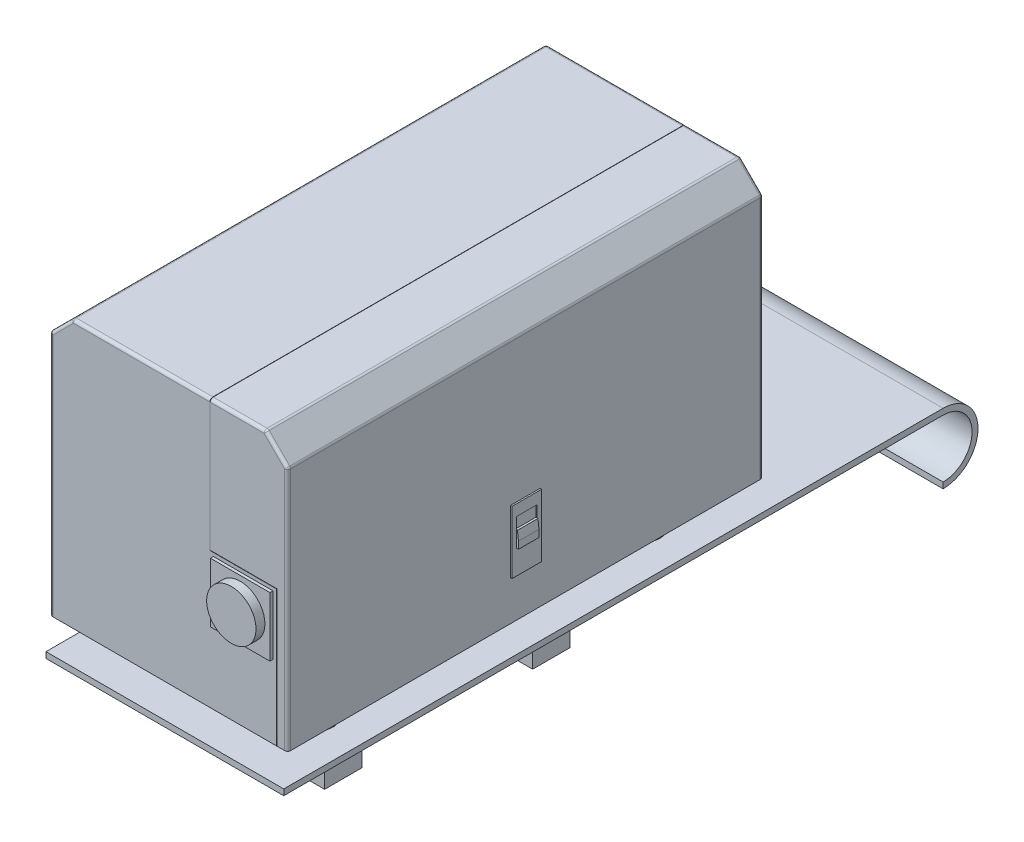
SolidWorks part; units mm, degrees
ref_plane "前视基准面" through (0, 0, 0) normal (0, 0, 1) x (1, 0, 0)
ref_plane "上视基准面" through (0, 0, 0) normal (0, 1, 0) x (1, 0, 0)
ref_plane "右视基准面" through (0, 0, 0) normal (1, 0, 0) x (0, 0, -1)
sketch "草图1" plane through (0, 0, 0) normal (0, 1, 0) x (1, 0, 0)
  line L1 (-80, -160) -> (80, -160)
  line L2 (-80, -160) -> (-80, 160)
  line L3 (-80, 160) -> (80, 160)
  line L4 (80, -160) -> (80, 160)
  line L5 (-80, -160) -> (80, 160) construction
  line L6 (-80, 160) -> (80, -160) construction
  point P0 (0, 0)
  dimension "D1" = 160
  dimension "D2" = 320
extrude "凸台-拉伸1" add sketch "草图1" along normal blind 180
sketch "草图2" plane through (0, 0, 160) normal (0, 0, 1) x (1, 0, 0)
  line L0 (27.8672, 180) -> (27.8672, 91.7238)
  line L1 (-80, 180) -> (80, 180) construction
  line L2 (27.8672, 91.7238) -> (72.7076, 91.7238)
  line L3 (72.7076, 91.7238) -> (72.7076, 0)
  line L4 (-80, 0) -> (80, 0) construction
extrude "切除-拉伸-薄壁3" cut sketch "草图2" along normal blind 0.2 and the other way through all thin
chamfer "倒角1" distance 15 angle 45 1 edges at (80, 180, 0)
chamfer "倒角2" distance 15 angle 45 1 edges at (-80, 180, 0)
fillet "圆角1" radius 2 8 edges at (80, 82.5, -160) (46.4336, 180, -160) (72.5, 172.5, -160) (80, 165, 0) (65, 180, 0) (72.5, 172.5, 160) (46.4336, 180, 160) (80, 82.5, 160)
fillet "圆角2" radius 2 8 edges at (-80, 82.5, -160) (-80, 165, 0) (-80, 82.5, 160) (-72.5, 172.5, -160) (-18.6664, 180, -160) (-65, 180, 0) (-72.5, 172.5, 160) (-18.6664, 180, 160)
sketch "草图3" plane through (80, 0, 0) normal (1, 0, 0) x (0, 0, -1)
  line L0 (0, 0) -> (0, 146.6557) construction
  line L2 (-9.9147, 26.7345) -> (9.9147, 26.7345)
  line L3 (-9.9147, 26.7345) -> (-9.9147, 68.9115)
  line L4 (-9.9147, 68.9115) -> (9.9147, 68.9115)
  line L5 (9.9147, 26.7345) -> (9.9147, 68.9115)
  line L6 (-9.9147, 26.7345) -> (9.9147, 68.9115) construction
  line L7 (-9.9147, 68.9115) -> (9.9147, 26.7345) construction
  point P3 (0, 47.823)
extrude "凸台-拉伸2" add sketch "草图3" along normal blind 1 separate body
sketch "草图4" plane through (81, 0, 0) normal (1, 0, 0) x (0, 0, -1)
  line L0 (0, 68.9115) -> (0, 26.3346) construction
  line L1 (9.9147, 68.9115) -> (-9.9147, 68.9115) construction
  line L3 (-6.9024, 42.8775) -> (6.9024, 42.8775)
  line L4 (-6.9024, 42.8775) -> (-6.9024, 61.4437)
  line L5 (-6.9024, 61.4437) -> (6.9024, 61.4437)
  line L6 (6.9024, 42.8775) -> (6.9024, 61.4437)
  line L7 (-6.9024, 42.8775) -> (6.9024, 61.4437) construction
  line L8 (-6.9024, 61.4437) -> (6.9024, 42.8775) construction
  point P5 (0, 52.1606)
extrude "切除-拉伸2" cut sketch "草图4" against normal blind 0.8
sketch "草图5" plane through (0, 0, 160) normal (0, 0, 1) x (1, 0, 0)
  line L0 (50.0874, 91.5238) -> (50.0874, 34.0941) construction
  line L1 (72.5076, 91.5238) -> (27.6672, 91.5238) construction
  line L3 (30.0874, 49.1617) -> (70.0874, 49.1617)
  line L4 (30.0874, 49.1617) -> (30.0874, 89.1617)
  line L5 (30.0874, 89.1617) -> (70.0874, 89.1617)
  line L6 (70.0874, 49.1617) -> (70.0874, 89.1617)
  line L7 (30.0874, 49.1617) -> (70.0874, 89.1617) construction
  line L8 (30.0874, 89.1617) -> (70.0874, 49.1617) construction
  point P4 (50.0874, 69.1617)
  dimension "D1" = 40
  dimension "D2" = 40
extrude "凸台-拉伸3" add sketch "草图5" along normal blind 2
sketch "草图6" plane through (0, 0, 162) normal (0, 0, 1) x (1, 0, 0)
  line L0 (50.0874, 89.1617) -> (50.0874, 49.1617) construction
  line L1 (70.0874, 89.1617) -> (30.0874, 89.1617) construction
  line L2 (30.0874, 49.1617) -> (70.0874, 49.1617) construction
  line L3 (70.0874, 69.1617) -> (30.0874, 69.1617) construction
  line L4 (70.0874, 49.1617) -> (70.0874, 89.1617) construction
  line L5 (30.0874, 89.1617) -> (30.0874, 49.1617) construction
  circle A0 centre (50.0874, 69.1617) radius 16.6027
extrude "凸台-拉伸4" add sketch "草图6" along normal blind 6
sketch "草图7" plane through (0, 0, 0) normal (0, -1, 0) x (1, 0, 0)
  line L1 (-50, -110) -> (50, -110) construction
  line L2 (-50, -110) -> (-50, 110) construction
  line L3 (-50, 110) -> (50, 110) construction
  line L4 (50, -110) -> (50, 110) construction
  line L5 (-50, -110) -> (50, 110) construction
  line L6 (-50, 110) -> (50, -110) construction
  circle A0 centre (-50, 110) radius 12
  circle A1 centre (50, 110) radius 12
  circle A2 centre (-50, -110) radius 12
  circle A3 centre (50, -110) radius 12
  point P0 (0, 0)
  dimension "D1" = 24
  dimension "D2" = 220
  dimension "D3" = 100
extrude "凸台-拉伸5" add sketch "草图7" along normal blind 20
chamfer "倒角3" distance 14 angle 6 4 edges at (-50, -20, -122) (50, -20, -122) (50, -20, 98) (-50, -20, 98)
sketch "草图9" plane through (0, 0, 0) normal (1, 0, 0) x (0, 0, -1)
  line L0 (-110, -20) -> (110, -20) construction
  line L1 (-120.5285, -20) -> (-99.4715, -20) construction
  line L2 (99.4715, -20) -> (120.5285, -20) construction
  line L3 (-162.6146, -20) -> (281.0711, -20)
  line L4 (-162.6146, -24) -> (281.0711, -24)
  line L5 (-162.6146, -20) -> (-162.6146, -24)
  line L6 (281.0711, -62.9888) -> (281.0711, -66.9888)
  arc A0 (281.0711, -20) -> (281.0711, -66.9888) centre (281.0711, -43.4944) cw
  arc A1 (281.0711, -24) -> (281.0711, -62.9888) centre (281.0711, -43.4944) cw
  arc A2 (281.0711, -24) -> (269.6435, -59.2881) centre (281.0711, -43.4944) cw construction
  arc A3 (281.0711, -20) -> (267.2987, -62.5287) centre (281.0711, -43.4944) cw construction
  dimension "D1" = 4
extrude "凸台-拉伸6" add sketch "草图9" along normal mid plane 160 separate body
sketch "草图10" plane through (0, -24, 0) normal (0, -1, 0) x (1, 0, 0)
  line L0 (80, 162.6146) -> (-80, 162.6146) construction
  line L1 (-70, 100.1146) -> (70, 100.1146)
  line L2 (-70, 100.1146) -> (-70, 125.1146)
  line L3 (-70, 125.1146) -> (70, 125.1146)
  line L4 (70, 100.1146) -> (70, 125.1146)
  line L5 (-70, 100.1146) -> (70, 125.1146) construction
  line L6 (-70, 125.1146) -> (70, 100.1146) construction
  line L7 (-70, -39.8854) -> (70, -39.8854)
  line L8 (-70, -39.8854) -> (-70, -14.8854)
  line L9 (-70, -14.8854) -> (70, -14.8854)
  line L10 (70, -39.8854) -> (70, -14.8854)
  line L11 (-70, -39.8854) -> (70, -14.8854) construction
  line L12 (-70, -14.8854) -> (70, -39.8854) construction
  point P0 (0, 112.6146)
  point P5 (0, -27.3854)
  dimension "D1" = 140
  dimension "D2" = 140
  dimension "D3" = 25
  dimension "D4" = 25
  dimension "D5" = 140
  dimension "D6" = 50
extrude "凸台-拉伸7" add sketch "草图10" along normal blind 20 separate body
sketch "草图11" plane through (0, -44, 0) normal (0, -1, 0) x (1, 0, 0)
  line L0 (0, 125.1146) -> (0, -39.8854) construction
  line L1 (70, 125.1146) -> (-70, 125.1146) construction
  line L2 (-70, -39.8854) -> (70, -39.8854) construction
  line L4 (-30, -27.3854) -> (30, -27.3854) construction
  line L5 (-30, -27.3854) -> (-30, 112.6146) construction
  line L6 (-30, 112.6146) -> (30, 112.6146) construction
  line L7 (30, -27.3854) -> (30, 112.6146) construction
  line L8 (-30, -27.3854) -> (30, 112.6146) construction
  line L9 (-30, 112.6146) -> (30, -27.3854) construction
  circle A0 centre (-30, 112.6146) radius 4
  circle A1 centre (30, 112.6146) radius 4
  circle A2 centre (30, -27.3854) radius 4
  circle A3 centre (-30, -27.3854) radius 4
  point P6 (0, 42.6146)
  dimension "D3" = 8
  dimension "D1" = 140
  dimension "D2" = 60
extrude "切除-拉伸3" cut sketch "草图11" against normal blind 30
sketch "草图13" plane through (80.2, 0, 0) normal (1, 0, 0) x (0, 0, -1)
  line L0 (-6.9024, 61.4437) -> (-6.9024, 42.8775) construction
  line L1 (6.9024, 42.8775) -> (-6.9024, 42.8775)
  line L2 (6.9024, 42.8775) -> (6.9024, 53.6776)
  line L3 (6.9024, 53.6776) -> (-6.9024, 53.6776)
  line L4 (-6.9024, 42.8775) -> (-6.9024, 53.6776)
extrude "凸台-拉伸8" add sketch "草图13" along normal blind 2
chamfer "倒角4" distance 6 angle 6 1 edges at (82.2, 53.6776, 0)
